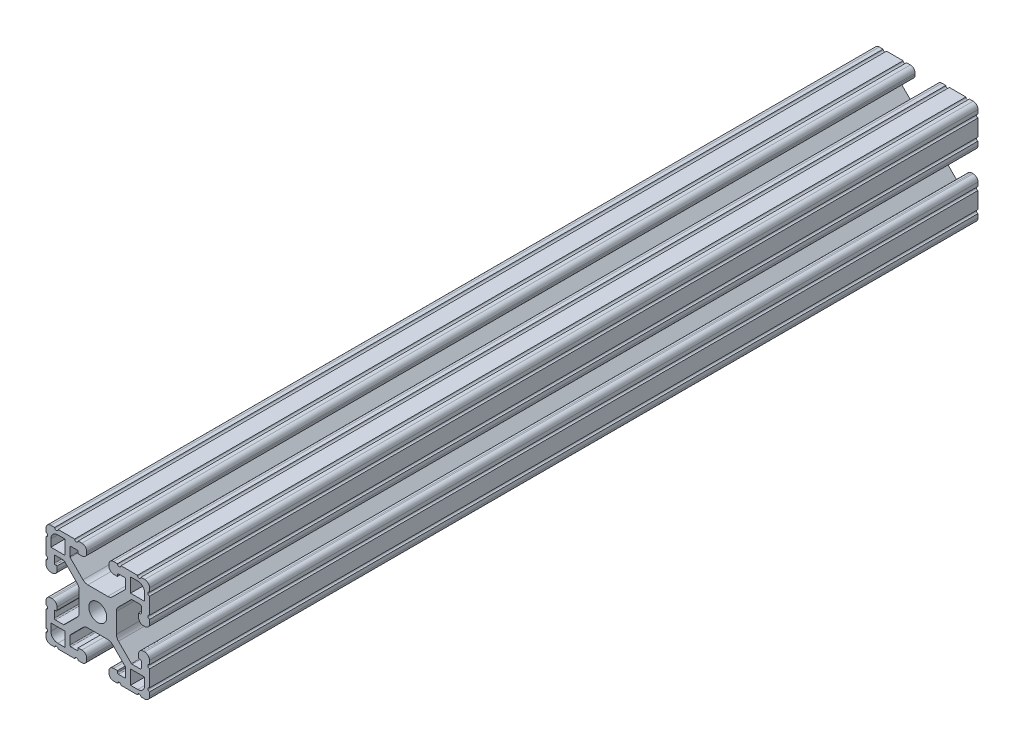
SolidWorks part; units mm, degrees
ref_plane "Front Plane" through (0, 0, 0) normal (0, 0, 1) x (1, 0, 0)
ref_plane "Top Plane" through (0, 0, 0) normal (0, 1, 0) x (1, 0, 0)
ref_plane "Right Plane" through (0, 0, 0) normal (1, 0, 0) x (0, 0, -1)
sketch "Sketch1" plane through (0, 0, 0) normal (0, 0, 1) x (1, 0, 0)
  line L0 (0, -19.05) -> (0, 19.05) construction
  line L1 (19.05, 0) -> (-19.05, 0) construction
  line L2 (4.064, 19.05) -> (-4.064, 19.05) construction
  line L3 (0, -6.858) -> (0, 6.858) construction
  line L4 (-4.064, 19.05) -> (-4.064, 14.986) construction
  line L5 (19.05, -10.287) -> (19.05, 10.287) construction
  line L6 (0, -3.302) -> (0, 3.302) construction
  point P4 (0, 0)
  point P8 (0, 0)
  point P11 (0, 19.05)
  point P14 (0, 0)
  point P18 (19.05, 0)
  point P21 (0, 0)
  dimension "Rail Width" = 38.1
  dimension "Rail Height" = 38.1
  dimension "T-Slot Width" = 8.128
  dimension "Thickness" = 4.064
  dimension "Opening Width" = 20.574
  dimension "Center Hole Diameter" = 6.604
  dimension "Slot Depth" = 12.192
sketch "Sketch2" plane through (0, 0, 0) normal (1, 0, 0) x (0, 0, -1)
  line L0 (-152.4, 0) -> (152.4, 0) construction
  line L1 (0, 19.05) -> (0, -19.05) construction
  line L2 (-25.4, 19.05) -> (25.4, 19.05) construction
  line L4 (3048, -19.05) -> (-3048, -19.05) construction
  point P0 (101.6, 0)
  point P3 (-101.6, 0)
  point P4 (0, 0)
  dimension "D1" = 50.8
  dimension "Rep Length" = 304.8
  dimension "D2" = 50.8
  dimension "Length Range [Min]" = 50.8
  dimension "Length Range [Max]" = 6096
sketch "Sketch3" plane through (0, 0, 0) normal (0, 0, 1) x (1, 0, 0)
  line L1 (19.05, -19.05) -> (-19.05, -19.05)
  line L2 (19.05, -19.05) -> (19.05, 19.05)
  line L3 (19.05, 19.05) -> (-19.05, 19.05)
  line L4 (-19.05, -19.05) -> (-19.05, 19.05)
  line L5 (19.05, -19.05) -> (-19.05, 19.05) construction
  line L6 (19.05, 19.05) -> (-19.05, -19.05) construction
  point P0 (0, 0)
extrude "Boss-Extrude1" add sketch "Sketch3" along normal up to vertex (152.4 mm away) and the other way up to vertex (152.4 mm away) up to point (0, 0, 152.4) other way up to point (0, 0, -152.4)
sketch "Sketch4" plane through (0, 0, 152.4) normal (0, 0, 1) x (1, 0, 0)
  line L4 (4.064, 14.986) -> (4.064, 19.05)
  line L5 (7.239, 14.986) -> (4.064, 14.986)
  line L6 (19.05, 0) -> (-19.05, 0) construction
  line L7 (4.7027, 6.858) -> (-4.7027, 6.858)
  line L8 (-4.7027, 6.858) -> (-10.287, 12.4423)
  line L37 (-19.05, 19.05) -> (-19.05, -19.05) construction
  line L38 (-19.05, -19.05) -> (19.05, -19.05) construction
  line L39 (-10.287, 12.4423) -> (-10.287, 16.002)
  line L40 (-10.287, 16.002) -> (-7.239, 16.002)
  line L41 (-7.239, 16.002) -> (-7.239, 14.986)
  line L42 (-7.239, 14.986) -> (-4.064, 14.986)
  line L43 (-4.064, 14.986) -> (-4.064, 19.05)
  line L44 (-4.064, 19.05) -> (4.064, 19.05)
  line L45 (0, 19.05) -> (0, 0) construction
  line L46 (-19.05, 19.05) -> (0, 0) construction
  line L47 (7.239, 16.002) -> (7.239, 14.986)
  line L48 (10.287, 16.002) -> (7.239, 16.002)
  line L49 (10.287, 12.4423) -> (10.287, 16.002)
  line L50 (4.7027, 6.858) -> (10.287, 12.4423)
  line L51 (-19.05, 0) -> (19.05, 0) construction
  line L52 (4.7027, -6.858) -> (10.287, -12.4423)
  line L53 (10.287, -12.4423) -> (10.287, -16.002)
  line L54 (10.287, -16.002) -> (7.239, -16.002)
  line L55 (7.239, -16.002) -> (7.239, -14.986)
  line L56 (-4.064, -19.05) -> (4.064, -19.05)
  line L57 (-4.064, -14.986) -> (-4.064, -19.05)
  line L58 (-7.239, -14.986) -> (-4.064, -14.986)
  line L59 (-7.239, -16.002) -> (-7.239, -14.986)
  line L60 (-10.287, -16.002) -> (-7.239, -16.002)
  line L61 (-10.287, -12.4423) -> (-10.287, -16.002)
  line L62 (-4.7027, -6.858) -> (-10.287, -12.4423)
  line L63 (4.7027, -6.858) -> (-4.7027, -6.858)
  line L64 (7.239, -14.986) -> (4.064, -14.986)
  line L65 (4.064, -14.986) -> (4.064, -19.05)
  line L66 (-6.858, -4.7027) -> (-12.4423, -10.287)
  line L67 (-12.4423, -10.287) -> (-16.002, -10.287)
  line L68 (-16.002, -10.287) -> (-16.002, -7.239)
  line L69 (-16.002, -7.239) -> (-14.986, -7.239)
  line L70 (-19.05, 4.064) -> (-19.05, -4.064)
  line L71 (-14.986, 4.064) -> (-19.05, 4.064)
  line L72 (-14.986, 7.239) -> (-14.986, 4.064)
  line L73 (-16.002, 7.239) -> (-14.986, 7.239)
  line L74 (-16.002, 10.287) -> (-16.002, 7.239)
  line L75 (-12.4423, 10.287) -> (-16.002, 10.287)
  line L76 (-6.858, 4.7027) -> (-12.4423, 10.287)
  line L77 (-6.858, -4.7027) -> (-6.858, 4.7027)
  line L78 (-14.986, -7.239) -> (-14.986, -4.064)
  line L79 (-14.986, -4.064) -> (-19.05, -4.064)
  line L80 (14.986, -4.064) -> (19.05, -4.064)
  line L81 (14.986, -7.239) -> (14.986, -4.064)
  line L82 (6.858, -4.7027) -> (6.858, 4.7027)
  line L83 (6.858, 4.7027) -> (12.4423, 10.287)
  line L84 (12.4423, 10.287) -> (16.002, 10.287)
  line L85 (16.002, 10.287) -> (16.002, 7.239)
  line L86 (16.002, 7.239) -> (14.986, 7.239)
  line L87 (14.986, 7.239) -> (14.986, 4.064)
  line L88 (14.986, 4.064) -> (19.05, 4.064)
  line L89 (19.05, 4.064) -> (19.05, -4.064)
  line L90 (16.002, -7.239) -> (14.986, -7.239)
  line L91 (16.002, -10.287) -> (16.002, -7.239)
  line L92 (12.4423, -10.287) -> (16.002, -10.287)
  line L93 (6.858, -4.7027) -> (12.4423, -10.287)
  line L94 (19.05, -19.05) -> (19.05, 19.05) construction
  line L95 (12.065, 17.272) -> (17.272, 17.272)
  line L96 (12.065, 17.272) -> (12.065, 12.065)
  line L97 (12.065, 12.065) -> (17.272, 12.065)
  line L98 (17.272, 17.272) -> (17.272, 12.065)
  line L99 (19.05, 19.05) -> (-19.05, 19.05) construction
  line L100 (17.272, -17.272) -> (17.272, -12.065)
  line L101 (12.065, -17.272) -> (17.272, -17.272)
  line L102 (12.065, -17.272) -> (12.065, -12.065)
  line L103 (12.065, -12.065) -> (17.272, -12.065)
  line L104 (-17.272, 17.272) -> (-17.272, 12.065)
  line L105 (-12.065, 12.065) -> (-17.272, 12.065)
  line L106 (-12.065, 17.272) -> (-12.065, 12.065)
  line L107 (-12.065, 17.272) -> (-17.272, 17.272)
  line L108 (-12.065, -12.065) -> (-17.272, -12.065)
  line L109 (-12.065, -17.272) -> (-12.065, -12.065)
  line L110 (-12.065, -17.272) -> (-17.272, -17.272)
  line L111 (-17.272, -17.272) -> (-17.272, -12.065)
  circle A5 centre (0, 0) radius 3.302
  point P21 (0, 6.858)
  point P23 (0, -6.858)
  point P38 (-6.858, 0)
  point P53 (6.858, 0)
  dimension "D1" = 20.574
  dimension "D2" = 3.048
  dimension "D3" = 3.048
  dimension "D4" = 3.048
  dimension "D5" = 1.778
  dimension "D6" = 1.778
  dimension "D7" = 1.778
extrude "Cut-Extrude1" cut sketch "Sketch4" against normal through all
sketch "Sketch5" plane through (0, 0, 152.4) normal (0, 0, 1) x (1, 0, 0)
  line L4 (-4.064, 19.05) -> (-19.05, 19.05) construction
  line L26 (-19.05, 19.05) -> (-19.05, 4.064) construction
  line L27 (-15.875, 19.05) -> (-14.605, 19.05)
  line L28 (-8.509, 19.05) -> (-7.239, 19.05)
  line L29 (-19.05, 15.875) -> (-19.05, 14.605)
  line L30 (-19.05, 8.509) -> (-19.05, 7.239)
  line L31 (8.509, 19.05) -> (7.239, 19.05)
  line L32 (15.875, 19.05) -> (14.605, 19.05)
  line L33 (19.05, 15.875) -> (19.05, 14.605)
  line L34 (19.05, 8.509) -> (19.05, 7.239)
  line L35 (19.05, -8.509) -> (19.05, -7.239)
  line L36 (19.05, -15.875) -> (19.05, -14.605)
  line L37 (15.875, -19.05) -> (14.605, -19.05)
  line L38 (8.509, -19.05) -> (7.239, -19.05)
  line L39 (-8.509, -19.05) -> (-7.239, -19.05)
  line L40 (-15.875, -19.05) -> (-14.605, -19.05)
  line L41 (-19.05, -15.875) -> (-19.05, -14.605)
  line L42 (-19.05, -8.509) -> (-19.05, -7.239)
  line L43 (19.05, 19.05) -> (4.064, 19.05) construction
  line L44 (19.05, 4.064) -> (19.05, 19.05) construction
  line L48 (-14.986, 4.064) -> (-19.05, 4.064) construction
  line L49 (-4.064, 14.986) -> (-4.064, 19.05) construction
  arc A8 (-15.875, 19.05) -> (-14.605, 19.05) centre (-15.24, 19.05) ccw
  arc A9 (-8.509, 19.05) -> (-7.239, 19.05) centre (-7.874, 19.05) ccw
  arc A10 (-19.05, 14.605) -> (-19.05, 15.875) centre (-19.05, 15.24) ccw
  arc A11 (-19.05, 7.239) -> (-19.05, 8.509) centre (-19.05, 7.874) ccw
  arc A12 (7.239, 19.05) -> (8.509, 19.05) centre (7.874, 19.05) ccw
  arc A13 (14.605, 19.05) -> (15.875, 19.05) centre (15.24, 19.05) ccw
  arc A14 (19.05, 15.875) -> (19.05, 14.605) centre (19.05, 15.24) ccw
  arc A15 (19.05, 8.509) -> (19.05, 7.239) centre (19.05, 7.874) ccw
  arc A16 (19.05, -7.239) -> (19.05, -8.509) centre (19.05, -7.874) ccw
  arc A17 (19.05, -14.605) -> (19.05, -15.875) centre (19.05, -15.24) ccw
  arc A18 (15.875, -19.05) -> (14.605, -19.05) centre (15.24, -19.05) ccw
  arc A19 (8.509, -19.05) -> (7.239, -19.05) centre (7.874, -19.05) ccw
  arc A20 (-7.239, -19.05) -> (-8.509, -19.05) centre (-7.874, -19.05) ccw
  arc A21 (-14.605, -19.05) -> (-15.875, -19.05) centre (-15.24, -19.05) ccw
  arc A22 (-19.05, -15.875) -> (-19.05, -14.605) centre (-19.05, -15.24) ccw
  arc A23 (-19.05, -8.509) -> (-19.05, -7.239) centre (-19.05, -7.874) ccw
  dimension "D2" = 0.635
  dimension "D4" = 3.81
  dimension "D5" = 3.81
  dimension "D1" = 3.81
  dimension "D3" = 3.81
  dimension "D7" = 4
extrude "Cut-Extrude2" cut sketch "Sketch5" against normal through all
fillet "Fillet1" radius 2.54 12 edges at (-6.858, 4.7027, 0) (-6.858, -4.7027, 0) (4.7027, -6.858, 0) (-4.7027, -6.858, 0) (6.858, -4.7027, 0) (6.858, 4.7027, 0) (4.7027, 6.858, 0) (-4.7027, 6.858, 0) (-17.272, 17.272, 0) (17.272, 17.272, 0) (17.272, -17.272, 0) (-17.272, -17.272, 0)
fillet "Fillet2" radius 1.778 20 edges at (19.05, -19.05, 0) (19.05, 19.05, 0) (-19.05, -19.05, 0) (-19.05, 19.05, 0) (-14.986, 4.064, 0) (-19.05, 4.064, 0) (-19.05, -4.064, 0) (-14.986, -4.064, 0) (-4.064, -19.05, 0) (-4.064, -14.986, 0) (4.064, -14.986, 0) (4.064, -19.05, 0) (19.05, -4.064, 0) (14.986, -4.064, 0) (19.05, 4.064, 0) (14.986, 4.064, 0) (4.064, 14.986, 0) (4.064, 19.05, 0) (-4.064, 19.05, 0) (-4.064, 14.986, 0)
fillet "Fillet3" radius 0.3969 24 edges at (-14.986, -7.239, 0) (-16.002, -10.287, 0) (-12.4423, -10.287, 0) (-12.4423, 10.287, 0) (-16.002, 7.239, 0) (-16.002, 10.287, 0) (-10.287, 12.4423, 0) (-7.239, 16.002, 0) (-10.287, 16.002, 0) (10.287, 16.002, 0) (7.239, 16.002, 0) (10.287, 12.4423, 0) (16.002, 10.287, 0) (12.4423, 10.287, 0) (16.002, 7.239, 0) (16.002, -7.239, 0) (16.002, -10.287, 0) (12.4423, -10.287, 0) (10.287, -12.4423, 0) (10.287, -16.002, 0) (7.239, -16.002, 0) (-7.239, -16.002, 0) (-10.287, -12.4423, 0) (-10.287, -16.002, 0)
equation "\"D4@Sketch5\"=\"D3@Sketch5\""
equation "\"D5@Sketch5\"=\"D4@Sketch5\""
equation "\"D1@Sketch4\"=\"Opening Width@Sketch1\""
